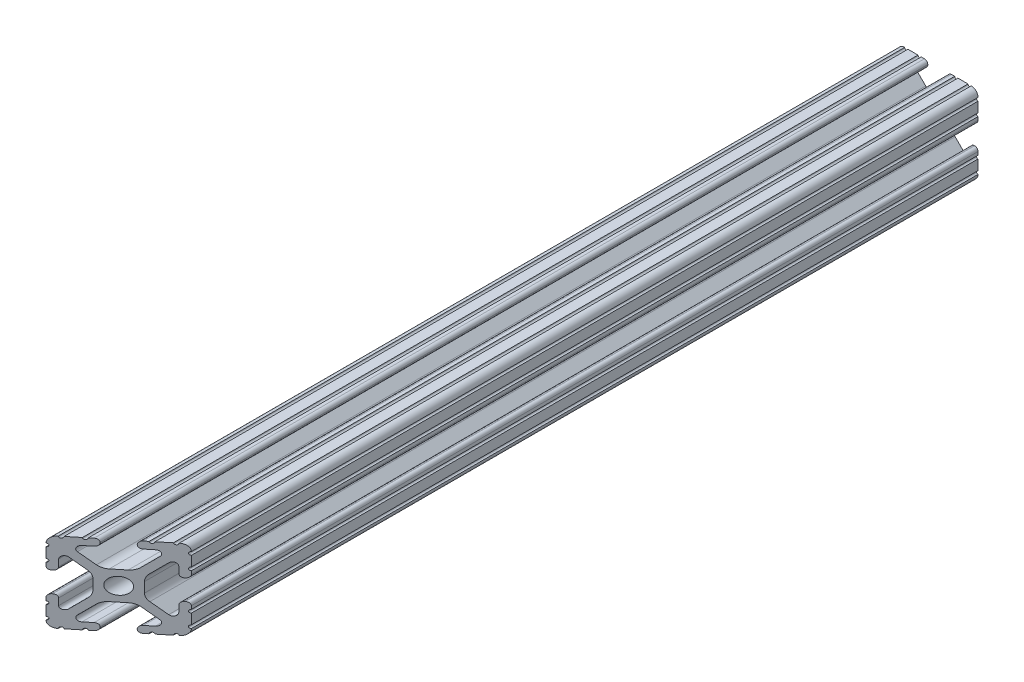
SolidWorks part; units mm, degrees
ref_plane "Front Plane" through (0, 0, 0) normal (0, 0, 1) x (1, 0, 0)
ref_plane "Top Plane" through (0, 0, 0) normal (0, 1, 0) x (1, 0, 0)
ref_plane "Right Plane" through (0, 0, 0) normal (1, 0, 0) x (0, 0, -1)
sketch "Sketch1" plane through (0, 0, 0) normal (0, 0, 1) x (1, 0, 0)
  line L88 (-7.1797, -8.6452) -> (-3.9523, -5.4237)
  line L89 (-1.7093, -4.4958) -> (1.7093, -4.4958)
  line L90 (3.9523, -5.4237) -> (7.1797, -8.6452)
  line L91 (6.4164, -10.4902) -> (4.2875, -10.4902)
  line L92 (3.2385, -11.5392) -> (3.2385, -11.651)
  line L93 (4.2875, -12.7) -> (5.3171, -12.7)
  line L94 (6.3331, -12.7) -> (9.5504, -12.7)
  line L95 (12.7, -9.5504) -> (12.7, -6.3331)
  line L96 (12.7, -5.3171) -> (12.7, -4.2875)
  line L97 (11.651, -3.2385) -> (11.5392, -3.2385)
  line L98 (10.4902, -4.2875) -> (10.4902, -6.4021)
  line L99 (8.7371, -7.1294) -> (5.441, -3.8408)
  line L100 (4.5085, -1.5932) -> (4.5085, 1.5932)
  line L101 (5.441, 3.8408) -> (8.7371, 7.1294)
  line L102 (10.4902, 6.4021) -> (10.4902, 4.2875)
  line L103 (11.5392, 3.2385) -> (11.651, 3.2385)
  line L104 (12.7, 4.2875) -> (12.7, 5.3171)
  line L105 (12.7, 6.3331) -> (12.7, 9.5504)
  line L106 (9.5504, 12.7) -> (6.3331, 12.7)
  line L107 (5.3171, 12.7) -> (4.2875, 12.7)
  line L108 (3.2385, 11.651) -> (3.2385, 11.5392)
  line L109 (4.2875, 10.4902) -> (6.4768, 10.4902)
  line L110 (7.207, 8.7244) -> (3.8983, 5.4232)
  line L111 (1.6558, 4.4958) -> (-1.6558, 4.4958)
  line L112 (-3.8983, 5.4232) -> (-7.207, 8.7244)
  line L113 (-6.4768, 10.4902) -> (-4.2875, 10.4902)
  line L114 (-3.2385, 11.5392) -> (-3.2385, 11.651)
  line L115 (-4.2875, 12.7) -> (-5.3171, 12.7)
  line L116 (-6.3331, 12.7) -> (-9.5504, 12.7)
  line L117 (-12.7, 9.5504) -> (-12.7, 6.3331)
  line L118 (-12.7, 5.3171) -> (-12.7, 4.2875)
  line L119 (-11.651, 3.2385) -> (-11.5392, 3.2385)
  line L120 (-10.4902, 4.2875) -> (-10.4902, 6.4021)
  line L121 (-8.7371, 7.1294) -> (-5.441, 3.8408)
  line L122 (-4.5085, 1.5932) -> (-4.5085, -1.5932)
  line L123 (-5.441, -3.8408) -> (-8.7371, -7.1294)
  line L124 (-10.4902, -6.4021) -> (-10.4902, -4.2875)
  line L125 (-11.5392, -3.2385) -> (-11.651, -3.2385)
  line L126 (-12.7, -4.2875) -> (-12.7, -5.3171)
  line L127 (-12.7, -6.3331) -> (-12.7, -9.5504)
  line L128 (-9.5504, -12.7) -> (-6.3331, -12.7)
  line L129 (-5.3171, -12.7) -> (-4.2875, -12.7)
  line L130 (-3.2385, -11.651) -> (-3.2385, -11.5392)
  line L131 (-4.2875, -10.4902) -> (-6.4164, -10.4902)
  circle A1 centre (0, 0) radius 2.6035
  arc A104 (-7.1797, -8.6452) -> (-6.4164, -10.4902) centre (-6.4164, -9.4098) ccw
  arc A105 (-1.7093, -4.4958) -> (-3.9523, -5.4237) centre (-1.7093, -7.6708) ccw
  arc A106 (3.9523, -5.4237) -> (1.7093, -4.4958) centre (1.7093, -7.6708) ccw
  arc A107 (6.4164, -10.4902) -> (7.1797, -8.6452) centre (6.4164, -9.4098) ccw
  arc A108 (4.2875, -10.4902) -> (3.2385, -11.5392) centre (4.2875, -11.5392) ccw
  arc A109 (3.2385, -11.651) -> (4.2875, -12.7) centre (4.2875, -11.651) ccw
  arc A110 (6.3331, -12.7) -> (5.3171, -12.7) centre (5.8251, -12.7) ccw
  arc A111 (10.5664, -12.6998) -> (9.5504, -12.7) centre (10.0584, -12.7) ccw
  arc A112 (10.5664, -12.6998) -> (12.6998, -10.5664) centre (10.5918, -10.5918) ccw
  arc A113 (12.7, -9.5504) -> (12.6998, -10.5664) centre (12.7, -10.0584) ccw
  arc A114 (12.7, -5.3171) -> (12.7, -6.3331) centre (12.7, -5.8251) ccw
  arc A115 (12.7, -4.2875) -> (11.651, -3.2385) centre (11.651, -4.2875) ccw
  arc A116 (11.5392, -3.2385) -> (10.4902, -4.2875) centre (11.5392, -4.2875) ccw
  arc A117 (8.7371, -7.1294) -> (10.4902, -6.4021) centre (9.4628, -6.4021) ccw
  arc A118 (4.5085, -1.5932) -> (5.441, -3.8408) centre (7.6835, -1.5932) ccw
  arc A119 (5.441, 3.8408) -> (4.5085, 1.5932) centre (7.6835, 1.5932) ccw
  arc A120 (10.4902, 6.4021) -> (8.7371, 7.1294) centre (9.4628, 6.4021) ccw
  arc A121 (10.4902, 4.2875) -> (11.5392, 3.2385) centre (11.5392, 4.2875) ccw
  arc A122 (11.651, 3.2385) -> (12.7, 4.2875) centre (11.651, 4.2875) ccw
  arc A123 (12.7, 6.3331) -> (12.7, 5.3171) centre (12.7, 5.8251) ccw
  arc A124 (12.6998, 10.5664) -> (12.7, 9.5504) centre (12.7, 10.0584) ccw
  arc A125 (12.6998, 10.5664) -> (10.5664, 12.6998) centre (10.5918, 10.5918) ccw
  arc A126 (9.5504, 12.7) -> (10.5664, 12.6998) centre (10.0584, 12.7) ccw
  arc A127 (5.3171, 12.7) -> (6.3331, 12.7) centre (5.8251, 12.7) ccw
  arc A128 (4.2875, 12.7) -> (3.2385, 11.651) centre (4.2875, 11.651) ccw
  arc A129 (3.2385, 11.5392) -> (4.2875, 10.4902) centre (4.2875, 11.5392) ccw
  arc A130 (7.207, 8.7244) -> (6.4768, 10.4902) centre (6.4768, 9.4563) ccw
  arc A131 (1.6558, 4.4958) -> (3.8983, 5.4232) centre (1.6558, 7.6708) ccw
  arc A132 (-3.8983, 5.4232) -> (-1.6558, 4.4958) centre (-1.6558, 7.6708) ccw
  arc A133 (-6.4768, 10.4902) -> (-7.207, 8.7244) centre (-6.4768, 9.4563) ccw
  arc A134 (-4.2875, 10.4902) -> (-3.2385, 11.5392) centre (-4.2875, 11.5392) ccw
  arc A135 (-3.2385, 11.651) -> (-4.2875, 12.7) centre (-4.2875, 11.651) ccw
  arc A136 (-6.3331, 12.7) -> (-5.3171, 12.7) centre (-5.8251, 12.7) ccw
  arc A137 (-10.5664, 12.6998) -> (-9.5504, 12.7) centre (-10.0584, 12.7) ccw
  arc A138 (-10.5664, 12.6998) -> (-12.6998, 10.5664) centre (-10.5918, 10.5918) ccw
  arc A139 (-12.7, 9.5504) -> (-12.6998, 10.5664) centre (-12.7, 10.0584) ccw
  arc A140 (-12.7, 5.3171) -> (-12.7, 6.3331) centre (-12.7, 5.8251) ccw
  arc A141 (-12.7, 4.2875) -> (-11.651, 3.2385) centre (-11.651, 4.2875) ccw
  arc A142 (-11.5392, 3.2385) -> (-10.4902, 4.2875) centre (-11.5392, 4.2875) ccw
  arc A143 (-8.7371, 7.1294) -> (-10.4902, 6.4021) centre (-9.4628, 6.4021) ccw
  arc A144 (-4.5085, 1.5932) -> (-5.441, 3.8408) centre (-7.6835, 1.5932) ccw
  arc A145 (-5.441, -3.8408) -> (-4.5085, -1.5932) centre (-7.6835, -1.5932) ccw
  arc A146 (-10.4902, -6.4021) -> (-8.7371, -7.1294) centre (-9.4628, -6.4021) ccw
  arc A147 (-10.4902, -4.2875) -> (-11.5392, -3.2385) centre (-11.5392, -4.2875) ccw
  arc A148 (-11.651, -3.2385) -> (-12.7, -4.2875) centre (-11.651, -4.2875) ccw
  arc A149 (-12.7, -6.3331) -> (-12.7, -5.3171) centre (-12.7, -5.8251) ccw
  arc A150 (-12.6998, -10.5664) -> (-12.7, -9.5504) centre (-12.7, -10.0584) ccw
  arc A151 (-12.6998, -10.5664) -> (-10.5664, -12.6998) centre (-10.5918, -10.5918) ccw
  arc A152 (-9.5504, -12.7) -> (-10.5664, -12.6998) centre (-10.0584, -12.7) ccw
  arc A153 (-5.3171, -12.7) -> (-6.3331, -12.7) centre (-5.8251, -12.7) ccw
  arc A154 (-4.2875, -12.7) -> (-3.2385, -11.651) centre (-4.2875, -11.651) ccw
  arc A155 (-3.2385, -11.5392) -> (-4.2875, -10.4902) centre (-4.2875, -11.5392) ccw
extrude "Boss-Extrude1" add sketch "Sketch1" along normal mid plane 289.56
sketch "Sketch2" plane through (0, 12.7, 0) normal (0, 1, 0) x (1, 0, 0)
  line L0 (-12.7, -144.78) -> (-12.7, 144.78) construction
  line L1 (-6.3331, -144.78) -> (-9.5504, -144.78) construction
  line L2 (9.5504, -144.78) -> (6.3331, -144.78) construction
  line L3 (12.7, -144.78) -> (12.7, 144.78) construction
  line L4 (-12.7, -144.78) -> (-12.7, 144.78) construction
  line L5 (-6.3331, -144.78) -> (-9.5504, -144.78) construction
  line L6 (9.5504, -144.78) -> (6.3331, -144.78) construction
  line L7 (12.7, -144.78) -> (12.7, 144.78) construction
  line L8 (12.7, -144.78) -> (-12.7, -144.78)
  line L9 (-12.7, -144.78) -> (-12.7, -125.5716)
  line L10 (-12.7, -125.5716) -> (12.7, -104.8312)
  line L11 (12.7, -104.8312) -> (12.7, -144.78)
extrude "Cut-Extrude1" cut sketch "Sketch2" against normal through all
